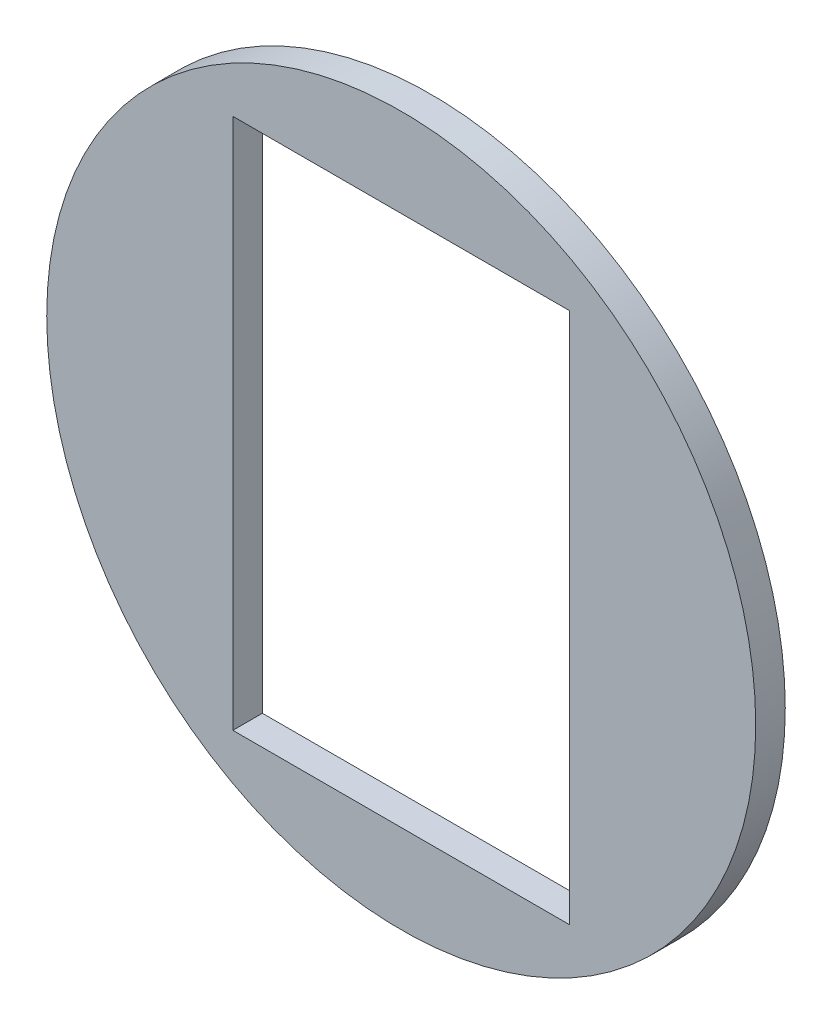
SolidWorks part; units mm, degrees
ref_plane "Front Plane" through (0, 0, 0) normal (0, 0, 1) x (1, 0, 0)
ref_plane "Top Plane" through (0, 0, 0) normal (0, 1, 0) x (1, 0, 0)
ref_plane "Right Plane" through (0, 0, 0) normal (1, 0, 0) x (0, 0, -1)
sketch "Sketch1" plane through (0, 0, 0) normal (0, 0, 1) x (1, 0, 0)
  line L1 (36.195, 57.15) -> (-36.195, 57.15)
  line L2 (36.195, 57.15) -> (36.195, -57.15)
  line L3 (36.195, -57.15) -> (-36.195, -57.15)
  line L4 (-36.195, 57.15) -> (-36.195, -57.15)
  line L5 (36.195, 57.15) -> (-36.195, -57.15) construction
  line L6 (36.195, -57.15) -> (-36.195, 57.15) construction
  circle A0 centre (0, 0) radius 76.2
  dimension "D1" = 152.4
  dimension "D2" = 114.3
  dimension "D3" = 72.39
extrude "Boss-Extrude1" add sketch "Sketch1" along normal blind 6.35 contours A0 | L2 L1 L4 L3
